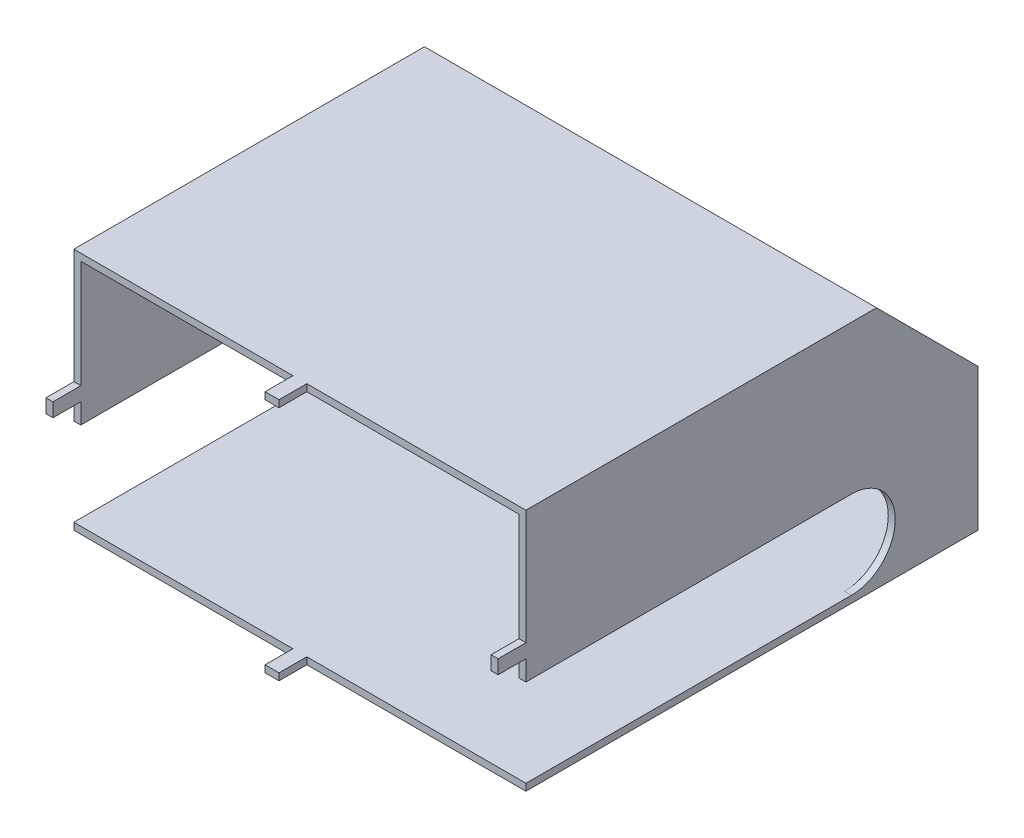
SolidWorks part; units mm, degrees
ref_plane "Face" through (0, 0, 0) normal (0, 0, 1) x (1, 0, 0)
ref_plane "Dessus" through (0, 0, 0) normal (0, 1, 0) x (1, 0, 0)
ref_plane "Droite" through (0, 0, 0) normal (1, 0, 0) x (0, 0, -1)
sketch "Esquisse1" plane through (0, 0, 0) normal (0, 0, 1) x (1, 0, 0)
  line L4 (-29.0877, 32.0672) -> (-61.5877, 32.0672)
  line L5 (-29.0877, 14.5672) -> (-29.0877, 32.0672)
  line L6 (-61.5877, 14.5672) -> (-29.0877, 14.5672)
  line L7 (-61.5877, 32.0672) -> (-61.5877, 14.5672)
  line L8 (-61.0877, 15.0672) -> (-29.5877, 15.0672)
  line L9 (-61.0877, 31.5672) -> (-61.0877, 15.0672)
  line L10 (-29.5877, 31.5672) -> (-61.0877, 31.5672)
  line L11 (-29.5877, 15.0672) -> (-29.5877, 31.5672)
  line L12 (-61.0877, 15.0672) -> (-29.5877, 15.0672)
  line L13 (-61.0877, 31.5672) -> (-61.0877, 15.0672)
  line L14 (-29.5877, 31.5672) -> (-61.0877, 31.5672)
  line L15 (-29.5877, 15.0672) -> (-29.5877, 31.5672)
  dimension "D1" = 0.5
  dimension "D2" = 0.5
extrude "Base-Extrusion" add sketch "Esquisse1" against normal blind 32
sketch "Esquisse3" plane through (-61.5877, 0, 0) normal (-1, 0, 0) x (0, 0, 1)
  line L0 (-32, 14.5672) -> (-32.5, 14.5672)
  line L1 (-32, 32.0672) -> (-32.5, 32.0672)
  line L2 (-32, 32.0672) -> (-32, 14.5672)
  line L4 (-32.5, 32.0672) -> (-32.5, 14.5672)
extrude "Boss.-Extru.1" add sketch "Esquisse3" against normal up to surface (32.5 mm away) up to face at (-29.0877, 23.3172, -16)
sketch "Esquisse4" plane through (-61.5877, 0, 0) normal (-1, 0, 0) x (0, 0, 1)
  line L0 (-23.4, 15.0672) -> (0.8173, 15.0672)
  line L1 (-23.4, 21.3672) -> (0.8173, 21.3672)
  line L2 (0.8173, 15.0672) -> (0.8173, 21.3672)
  arc A0 (-23.4, 21.3672) -> (-23.4, 15.0672) centre (-23.4, 18.2172) ccw
  dimension "D1" = 6.3
extrude "Enlèv. mat.-Extru.1" cut sketch "Esquisse4" against normal through all
sketch "Esquisse5" plane through (0, 0, 0) normal (0, 0, 1) x (1, 0, 0)
  line L0 (-44.8377, 15.0672) -> (-44.8377, 14.5672)
  line L1 (-29.0877, 23.8172) -> (-29.0877, 22.8172)
  line L2 (-44.8377, 32.0672) -> (-44.8377, 31.5672)
  line L3 (-45.8377, 32.0672) -> (-45.8377, 31.5672)
  line L5 (-45.8377, 14.5672) -> (-44.8377, 14.5672)
  line L6 (-45.8377, 31.5672) -> (-44.8377, 31.5672)
  line L7 (-45.8377, 15.0672) -> (-45.8377, 14.5672)
  line L8 (-45.8377, 15.0672) -> (-44.8377, 15.0672)
  line L9 (-61.5877, 23.8172) -> (-61.5877, 22.8172)
  line L10 (-29.5877, 23.8172) -> (-29.5877, 22.8172)
  line L12 (-29.5877, 23.8172) -> (-29.0877, 23.8172)
  line L13 (-29.5877, 22.8172) -> (-29.0877, 22.8172)
  line L15 (-45.8377, 32.0672) -> (-44.8377, 32.0672)
  line L16 (-61.5877, 23.8172) -> (-61.0877, 23.8172)
  line L17 (-61.5877, 22.8172) -> (-61.0877, 22.8172)
  line L18 (-61.0877, 23.8172) -> (-61.0877, 22.8172)
extrude "Boss.-Extru.2" add sketch "Esquisse5" along normal blind 2
sketch "Esquisse6" plane through (-61.5877, 0, 0) normal (-1, 0, 0) x (0, 0, 1)
  line L0 (-41.5269, 26.4372) -> (-29.2035, 38.7607)
  line L2 (-35.8285, 20.7388) -> (-23.5051, 33.0622)
  line L4 (-35.8285, 20.7388) -> (-41.5269, 26.4372)
  line L5 (-23.5051, 33.0622) -> (-29.2035, 38.7607)
extrude "Enlèv. mat.-Extru.2" cut sketch "Esquisse6" against normal blind 35.6937
sketch "Esquisse7" plane through (-61.5877, 0, 0) normal (-1, 0, 0) x (0, 0, 1)
  line L0 (-32.5, 24.0672) -> (-24.5, 32.0672)
  line L1 (-32.5, 24.7744) -> (-25.2071, 32.0672)
  line L2 (-32.5, 24.0672) -> (-32.5, 24.7744)
  line L3 (-24.5, 32.0672) -> (-25.2071, 32.0672)
  line L4 (-32.8536, 24.4208) -> (-24.8536, 32.4208) construction
extrude "Extrusion2" add sketch "Esquisse7" against normal up to vertex (32.5 mm away)
